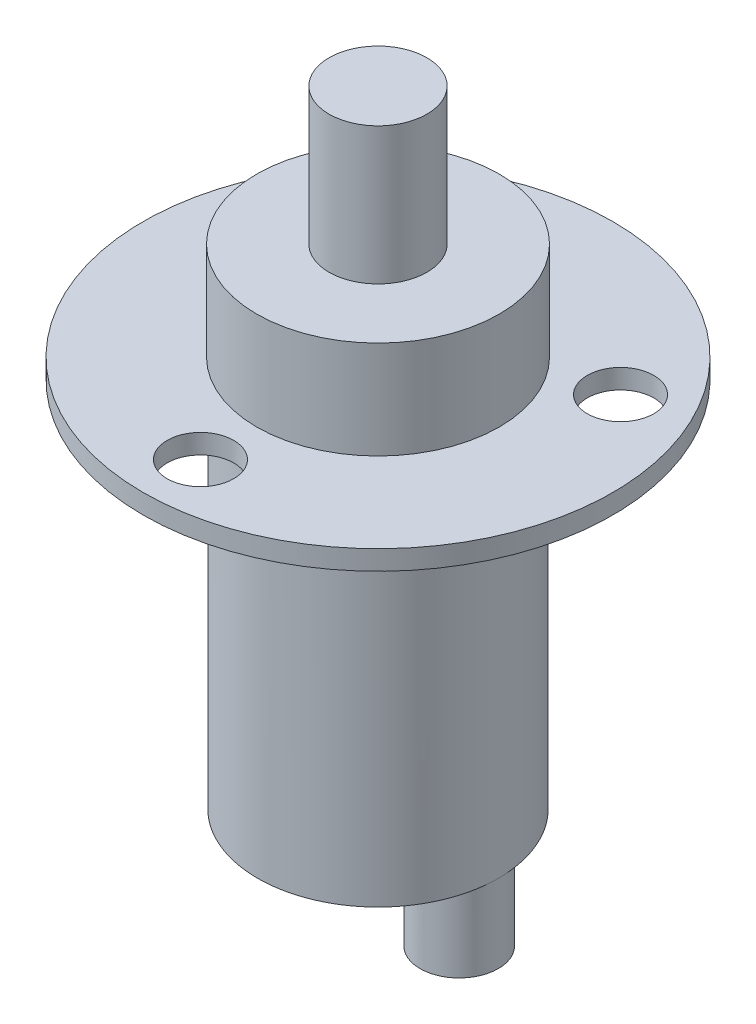
SolidWorks part; units mm, degrees
ref_plane "Front Plane" through (0, 0, 0) normal (0, 0, 1) x (1, 0, 0)
ref_plane "Top Plane" through (0, 0, 0) normal (0, 1, 0) x (1, 0, 0)
ref_plane "Right Plane" through (0, 0, 0) normal (1, 0, 0) x (0, 0, -1)
sketch "Sketch1" plane through (0, 0, 0) normal (0, 1, 0) x (1, 0, 0)
  circle A0 centre (0, 0) radius 6.15
  dimension "D1" = 12.3
extrude "Boss-Extrude1" add sketch "Sketch1" along normal blind 19
sketch "Sketch2" plane through (0, 19, 0) normal (0, 1, 0) x (1, 0, 0)
  circle A0 centre (0, 0) radius 12
  dimension "D1" = 24
extrude "Boss-Extrude2" add sketch "Sketch2" along normal blind 1
sketch "Sketch3" plane through (0, 20, 0) normal (0, 1, 0) x (1, 0, 0)
  circle A0 centre (0, 0) radius 6.2
  dimension "D1" = 12.4
extrude "Boss-Extrude3" add sketch "Sketch3" along normal blind 5
sketch "Sketch4" plane through (0, 25, 0) normal (0, 1, 0) x (1, 0, 0)
  circle A0 centre (0, 0) radius 2.5
  dimension "D1" = 5
extrude "Boss-Extrude4" add sketch "Sketch4" along normal blind 7
sketch "Sketch5" plane through (0, 0, 0) normal (0, -1, 0) x (1, 0, 0)
  circle A0 centre (-4.15, 0) radius 2
  circle A1 centre (4.15, 0) radius 2
  circle A2 centre (0, 0) radius 6.15 construction
  circle A3 centre (0, 0) radius 6.15 construction
  dimension "D1" = 4
extrude "Boss-Extrude5" add sketch "Sketch5" along normal blind 4
sketch "Sketch6" plane through (0, 19, 0) normal (0, -1, 0) x (1, 0, 0)
  circle A0 centre (0, 9.075) radius 1.7
  circle A1 centre (0, 0) radius 12 construction
  arc A2 (6.15, 0) -> (-6.15, 0) centre (0, 0) ccw construction
  circle A3 centre (0, 0) radius 12
  arc A4 (6.15, 0) -> (-6.15, 0) centre (0, 0) ccw
  circle A5 centre (0, 0) radius 9.075 construction
  circle A6 centre (7.8592, -4.5375) radius 1.7
  circle A7 centre (-7.8592, -4.5375) radius 1.7
  point P16 (0, 0)
  dimension "D1" = 3.4
  dimension "D2" = 24
  dimension "D4" = 18.15
  dimension "D5" = 3
extrude "Cut-Extrude1" cut sketch "Sketch6" against normal through all contours A0 | A6 | A7
equation "\"D4@Sketch6\"=(\"D2@Sketch6\"+2*\"D3@Sketch6\")/2"
